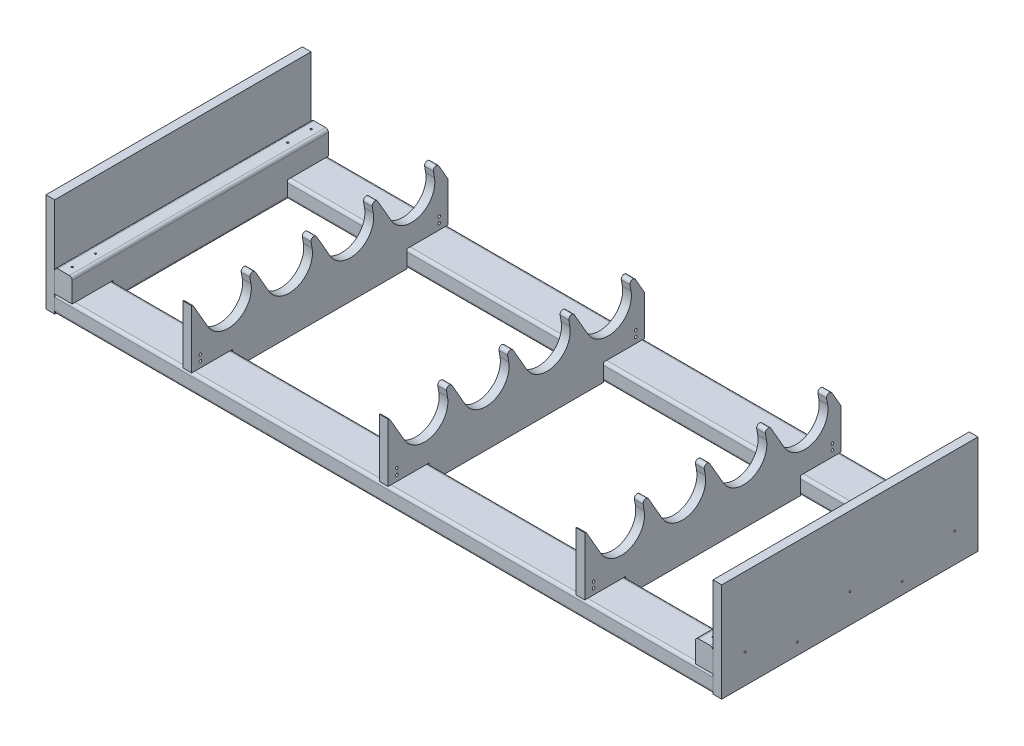
SolidWorks part; units mm, degrees
other "Left support panel"
other "Right support panel"
other "Left side panel"
other "Left 2x4"
other "Right 2x4"
other "Right side panel"
other "Front 2x4"
other "Back 2x4"
other "Middle support panel"
material "Pine"
ref_plane "Front Plane" through (0, 0, 0) normal (0, 0, 1) x (1, 0, 0)
ref_plane "Top Plane" through (0, 0, 0) normal (0, 1, 0) x (1, 0, 0)
ref_plane "Right Plane" through (0, 0, 0) normal (1, 0, 0) x (0, 0, -1)
sketch "Sketch1" plane through (0, 0, 0) normal (0, 1, 0) x (1, 0, 0)
  line L0 (0, 190.5) -> (0, -190.5) construction
  line L1 (-717.55, 190.5) -> (717.55, 190.5)
  line L2 (-717.55, 190.5) -> (-717.55, 279.4)
  line L3 (-717.55, 279.4) -> (717.55, 279.4)
  line L4 (717.55, 190.5) -> (717.55, 279.4)
  line L5 (717.55, -190.5) -> (-717.55, -190.5)
  line L6 (717.55, -190.5) -> (717.55, -279.4)
  line L7 (717.55, -279.4) -> (-717.55, -279.4)
  line L8 (-717.55, -190.5) -> (-717.55, -279.4)
  dimension "D1" = 558.8
  dimension "D2" = 1435.1
  dimension "D3" = 88.9
extrude "Boss-Extrude1" add sketch "Sketch1" along normal blind 38.1
fillet "Fillet2" radius 6.35 4 edges at (0, 38.1, 190.5) (0, 0, 190.5) (0, 0, 279.4) (0, 38.1, 279.4)
fillet "Fillet3" radius 6.35 4 edges at (0, 38.1, -279.4) (0, 0, -279.4) (0, 0, -190.5) (0, 38.1, -190.5)
sketch "Sketch5" plane through (717.55, 0, 0) normal (1, 0, 0) x (0, 0, -1)
  line L0 (-279.4, 31.75) -> (-279.4, 6.35) construction
  line L1 (-279.4, 88.9) -> (279.4, 88.9)
  line L2 (-279.4, 88.9) -> (-279.4, 38.1)
  line L3 (-190.5, 0) -> (190.5, 0)
  line L4 (279.4, 88.9) -> (279.4, 38.1)
  line L5 (-273.05, 0) -> (-196.85, 0) construction
  line L6 (279.4, 31.75) -> (279.4, 6.35) construction
  line L7 (-279.4, 38.1) -> (-190.5, 38.1)
  line L8 (-190.5, 38.1) -> (-190.5, 0)
  line L9 (279.4, 38.1) -> (190.5, 38.1)
  line L10 (190.5, 38.1) -> (190.5, 0)
  line L11 (196.85, 38.1) -> (273.05, 38.1) construction
  line L12 (190.5, 31.75) -> (190.5, 6.35) construction
  line L13 (-190.5, 31.75) -> (-190.5, 6.35) construction
  line L14 (-273.05, 38.1) -> (-196.85, 38.1) construction
  dimension "D1" = 88.9
extrude "Boss-Extrude4" add sketch "Sketch5" against normal blind 38.1 separate body
fillet "Fillet4" radius 6.35 4 edges at (717.55, 0, 0) (679.45, 0, 0) (679.45, 88.9, 0) (717.55, 88.9, 0)
mirror "Mirror6" about plane through (0, 0, 0) normal (1, 0, 0) of bodies 107
hole_wizard "Tap Drill for #10-24 Tap1" positions "Sketch6" profile "Sketch8" hole size "#10-24" standard "ANSI Inch"
sketch "Sketch6" plane through (0, 88.9, 0) normal (0, 1, 0) x (1, 0, 0)
  line L1 (-698.5, -209.55) -> (-698.5, -260.35) construction
  line L3 (698.5, -209.55) -> (698.5, -260.35) construction
  line L5 (698.5, 260.35) -> (698.5, 209.55) construction
  line L7 (-698.5, 260.35) -> (-698.5, 209.55) construction
  line L9 (717.55, -279.4) -> (-717.55, -279.4) construction
  line L10 (-717.55, -190.5) -> (717.55, -190.5) construction
  line L11 (-717.55, 279.4) -> (717.55, 279.4) construction
  line L12 (717.55, 279.4) -> (717.55, -279.4) construction
  line L13 (-717.55, 279.4) -> (-717.55, -279.4) construction
  point P0 (698.5, -260.35)
  point P2 (698.5, -209.55)
  point P4 (698.5, 209.55)
  point P6 (698.5, 260.35)
  point P8 (-698.5, 260.35)
  point P10 (-698.5, 209.55)
  point P12 (-698.5, -209.55)
  point P14 (-698.5, -260.35)
  point P33 (698.5, -234.95)
  point P34 (-698.5, -234.95)
  point P35 (-698.5, 234.95)
  point P36 (698.5, 234.95)
  dimension "D1" = 19.05
  dimension "D2" = 19.05
  dimension "D3" = 19.05
  dimension "D4" = 19.05
  dimension "D5" = 19.05
sketch "Sketch8" plane through (698.5, 88.9, 260.35) normal (1, 0, 0) x (0, 0, 1)
  line L0 (0, 0) -> (0, 77.3408)
  line L1 (0, 77.3408) -> (1.8986, 76.2)
  line L2 (1.8986, 76.2) -> (1.8986, 0)
  line L5 (1.8986, 0) -> (0, 0)
  line L10 (0, 77.3408) -> (-1.8987, 76.2) construction
  line L11 (0, -6.35) -> (0, 107.95) construction
  dimension "Hole Dia." = 3.7973
  dimension "Hole Depth" = 76.2
  dimension "Drill Angle" = 118
sketch "Sketch2" plane through (717.55, 0, 0) normal (1, 0, 0) x (0, 0, -1)
  line L0 (-279.4, 31.75) -> (-279.4, 6.35) construction
  line L1 (-279.4, 0) -> (279.4, 0)
  line L2 (-279.4, 0) -> (-279.4, 215.9)
  line L3 (-279.4, 215.9) -> (279.4, 215.9)
  line L4 (279.4, 0) -> (279.4, 215.9)
  line L5 (-273.05, 0) -> (-196.85, 0) construction
  line L6 (279.4, 31.75) -> (279.4, 6.35) construction
  dimension "D1" = 215.9
extrude "Boss-Extrude2" add sketch "Sketch2" along normal blind 19.05 separate body
mirror "Mirror2" about plane through (0, 0, 0) normal (1, 0, 0) of bodies 103
hole_wizard "Tap Drill for #10-24 Tap2" positions "Sketch9" profile "Sketch10" hole size "#10-24" standard "ANSI Inch"
sketch "Sketch9" plane through (736.6, 0, 0) normal (1, 0, 0) x (0, 0, -1)
  line L0 (-228.6, 63.5) -> (0, 63.5) construction
  line L1 (0, 63.5) -> (228.6, 63.5) construction
  line L3 (-114.3, 25.4) -> (114.3, 25.4) construction
  point P0 (-228.6, 63.5)
  point P2 (-114.3, 25.4)
  point P4 (0, 63.5)
  point P6 (114.3, 25.4)
  point P8 (228.6, 63.5)
  point P21 (0, 25.4)
  dimension "D1" = 25.4
  dimension "D2" = 38.1
  dimension "D3" = 228.6
sketch "Sketch10" plane through (736.6, 63.5, 228.6) normal (0, 1, 0) x (0, 0, -1)
  line L0 (0, 0) -> (0, 39.2408)
  line L1 (0, 39.2408) -> (1.8986, 38.1)
  line L2 (1.8986, 38.1) -> (1.8986, 0)
  line L5 (1.8986, 0) -> (0, 0)
  line L10 (0, 39.2408) -> (-1.8987, 38.1) construction
  line L11 (0, -6.35) -> (0, 107.95) construction
  dimension "Hole Dia." = 3.7973
  dimension "Hole Depth" = 38.1
  dimension "Drill Angle" = 118
hole_wizard "Tap Drill for #10-24 Tap3" positions "Sketch11" profile "Sketch12" hole size "#10-24" standard "ANSI Inch"
sketch "Sketch11" plane through (-736.6, 0, 0) normal (-1, 0, 0) x (0, 0, 1)
  point P0 (-228.6, 63.5)
  point P3 (-114.3, 25.4)
  point P6 (0, 63.5)
  point P9 (114.3, 25.4)
  point P12 (228.6, 63.5)
sketch "Sketch12" plane through (-736.6, 63.5, -228.6) normal (0, 1, 0) x (0, 0, 1)
  line L0 (0, 0) -> (0, 39.2408)
  line L1 (0, 39.2408) -> (1.8986, 38.1)
  line L2 (1.8986, 38.1) -> (1.8986, 0)
  line L5 (1.8986, 0) -> (0, 0)
  line L10 (0, 39.2408) -> (-1.8987, 38.1) construction
  line L11 (0, -6.35) -> (0, 107.95) construction
  dimension "Hole Dia." = 3.7973
  dimension "Hole Depth" = 38.1
  dimension "Drill Angle" = 118
ref_plane "Plane1" through (514.35, 0, 0) normal (-1, 0, 0) x (0, 0, 1)
sketch "Sketch3" plane through (514.35, 0, 0) normal (-1, 0, 0) x (0, 0, 1)
  line L0 (-66.675, 133.35) -> (66.675, 133.35) construction
  circle A0 centre (-200.025, 133.35) radius 50.8
  circle A1 centre (-66.675, 133.35) radius 50.8
  circle A2 centre (66.675, 133.35) radius 50.8
  circle A3 centre (200.025, 133.35) radius 50.8
  circle A4 centre (-200.025, 133.35) radius 127 construction
  circle A5 centre (66.675, 133.35) radius 127 construction
  circle A6 centre (-66.675, 133.35) radius 127 construction
  circle A7 centre (200.025, 133.35) radius 127 construction
  point P11 (-60.325, 133.35)
  point P12 (0, 133.35)
  point P13 (-73.025, 133.35)
  dimension "D1" = 101.6
  dimension "D2" = 76.2
  dimension "D3" = 133.35
  dimension "D4" = 133.35
  dimension "D5" = 133.35
  dimension "D6" = 12.7
  dimension "D7" = 133.35
ref_plane "Plane2" through (438.15, 0, 0) normal (-1, 0, 0) x (0, 0, 1)
sketch "Sketch4" plane through (438.15, 0, 0) normal (-1, 0, 0) x (0, 0, 1)
  line L0 (110.6691, 107.95) -> (158.6015, 190.9714)
  line L1 (275.822, 163.0342) -> (244.0191, 107.95)
  line L2 (-22.6809, 107.95) -> (25.2515, 190.9714)
  line L3 (-156.0309, 107.95) -> (-108.0985, 190.9714)
  line L4 (273.05, 38.1) -> (196.85, 38.1) construction
  line L5 (149.9968, 142.1713) -> (158.6015, 190.9714)
  line L6 (16.6468, 142.1713) -> (25.2515, 190.9714)
  line L7 (-116.7032, 142.1713) -> (-108.0985, 190.9714)
  line L8 (-250.0532, 142.1713) -> (-241.4485, 190.9714)
  line L9 (-190.5, 38.1) -> (-279.4, 38.1) construction
  line L10 (-279.4, 38.1) -> (-190.5, 38.1)
  line L11 (-190.5, 6.35) -> (-190.5, 38.1) construction
  line L12 (-190.5, 38.1) -> (-190.5, 0)
  line L13 (279.4, 0) -> (279.4, 215.9)
  line L14 (279.4, 215.9) -> (-279.4, 215.9)
  line L15 (-279.4, 215.9) -> (-279.4, 0)
  line L16 (-279.4, 0) -> (279.4, 0)
  line L17 (279.4, 38.1) -> (279.4, 165.1)
  line L18 (279.4, 215.9) -> (-279.4, 215.9) construction
  line L19 (-279.4, 190.9714) -> (-279.4, 38.1)
  line L20 (-190.5, 0) -> (190.5, 0)
  line L21 (190.5, 38.1) -> (190.5, 6.35) construction
  line L22 (190.5, 0) -> (190.5, 38.1)
  line L23 (279.4, 38.1) -> (190.5, 38.1) construction
  line L24 (190.5, 38.1) -> (279.4, 38.1)
  line L25 (-241.4485, 190.9714) -> (-279.4, 190.9714)
  line L26 (-279.4, 215.9) -> (-279.4, 190.9714) construction
  line L27 (279.4, 169.2315) -> (279.4, 215.9) construction
  line L28 (279.4, 169.2315) -> (275.822, 163.0342) construction
  line L29 (279.4, 165.1) -> (279.4, 169.2315) construction
  arc A0 (-156.0309, 107.95) -> (-250.0532, 142.1713) centre (-200.025, 133.35) ccw construction
  circle A1 centre (200.025, 133.35) radius 50.8
  arc A2 (149.9968, 142.1713) -> (244.0191, 107.95) centre (200.025, 133.35) ccw
  circle A3 centre (66.675, 133.35) radius 50.8
  arc A4 (16.6468, 142.1713) -> (110.6691, 107.95) centre (66.675, 133.35) ccw
  circle A5 centre (-66.675, 133.35) radius 50.8
  arc A6 (-116.7032, 142.1713) -> (-22.6809, 107.95) centre (-66.675, 133.35) ccw
  circle A7 centre (-200.025, 133.35) radius 50.8
  arc A8 (-250.0532, 142.1713) -> (-156.0309, 107.95) centre (-200.025, 133.35) ccw
  arc A9 (-22.6809, 107.95) -> (-116.7032, 142.1713) centre (-66.675, 133.35) ccw construction
  arc A10 (110.6691, 107.95) -> (16.6468, 142.1713) centre (66.675, 133.35) ccw construction
  arc A11 (244.0191, 107.95) -> (149.9968, 142.1713) centre (200.025, 133.35) ccw construction
  arc A12 (275.822, 163.0342) -> (279.4, 165.1) centre (279.4, 160.9685) cw
  dimension "D5" = 60
  dimension "D6" = 20
  dimension "D8" = 165.1
  dimension "D1" = 0
  dimension "D2" = 0
  dimension "D3" = 0
  dimension "D4" = 0
  dimension "D7" = 0
extrude "Boss-Extrude3" add sketch "Sketch4" along normal blind 19.05 separate body
sketch "Sketch15" plane through (419.1, 0, 0) normal (-1, 0, 0) x (0, 0, 1)
  line L3 (-108.0985, 190.9714) -> (-156.0309, 107.95) construction
  line L4 (-241.4485, 190.9714) -> (-384.175, 190.9714)
  line L5 (-384.175, 190.9714) -> (-384.175, 133.35)
  line L8 (-241.4485, 190.9714) -> (-279.4, 190.9714) construction
  line L10 (-333.375, 133.35) -> (-200.025, 133.35) construction
  line L11 (-200.025, 133.35) -> (-66.675, 133.35) construction
  line L12 (-289.3809, 107.95) -> (-241.4485, 190.9714)
  arc A0 (-289.3809, 107.95) -> (-384.175, 133.35) centre (-333.375, 133.35) ccw construction
  circle A4 centre (-200.025, 133.35) radius 50.8 construction
  circle A6 centre (-66.675, 133.35) radius 50.8 construction
  arc A7 (-250.0532, 142.1713) -> (-156.0309, 107.95) centre (-200.025, 133.35) ccw construction
  arc A8 (-116.7032, 142.1713) -> (-22.6809, 107.95) centre (-66.675, 133.35) ccw construction
  arc A9 (-384.175, 133.35) -> (-289.3809, 107.95) centre (-333.375, 133.35) ccw
extrude "Cut-Extrude1" cut sketch "Sketch15" against normal up to next (19.05 mm away)
fillet "Fillet1" radius 6.35 5 edges at (428.625, 190.9714, -108.0985) (428.625, 190.9714, 25.2515) (428.625, 190.9714, 158.6015) (428.625, 125.2374, -279.4) (428.625, 190.9714, -241.4485)
hole_wizard "#10 Clearance Hole1" positions "Sketch13" profile "Sketch14" hole size "#10" standard "ANSI Inch" end condition up to next
sketch "Sketch13" plane through (438.15, 0, 0) normal (1, 0, 0) x (0, 0, -1)
  line L0 (260.35, 63.5) -> (260.35, 50.8) construction
  line L2 (-260.35, 63.5) -> (-260.35, 50.8) construction
  line L4 (-190.5, 38.1) -> (-279.4, 38.1) construction
  line L5 (-279.4, 38.1) -> (-279.4, 165.1) construction
  line L6 (279.4, 123.536) -> (279.4, 38.1) construction
  point P0 (-260.35, 50.8)
  point P2 (-260.35, 63.5)
  point P4 (260.35, 50.8)
  point P6 (260.35, 63.5)
  dimension "D1" = 12.7
  dimension "D2" = 12.7
  dimension "D3" = 19.05
  dimension "D4" = 19.05
sketch "Sketch14" plane through (438.15, 50.8, 260.35) normal (0, 1, 0) x (0, 0, -1)
  line L0 (0, 0) -> (0, 19.051)
  line L1 (0, 19.051) -> (2.8067, 19.051)
  line L2 (2.8067, 19.051) -> (2.8067, 0)
  line L5 (2.8067, 0) -> (0, 0)
  line L11 (0, -6.35) -> (0, 107.95) construction
  dimension "Thru Hole Dia." = 5.6134
  dimension "Thru Hole Depth" = 19.051
mirror "Mirror4" about plane through (0, 0, 0) normal (1, 0, 0) of bodies 117 105 119
move or copy body "Body-Move/Copy1" bodies to move or copy 117 copy yes number of copies 1 translate (-428.625, 0, 0) parameters "D1"=428.625, "D2"=0, "D3"=0
